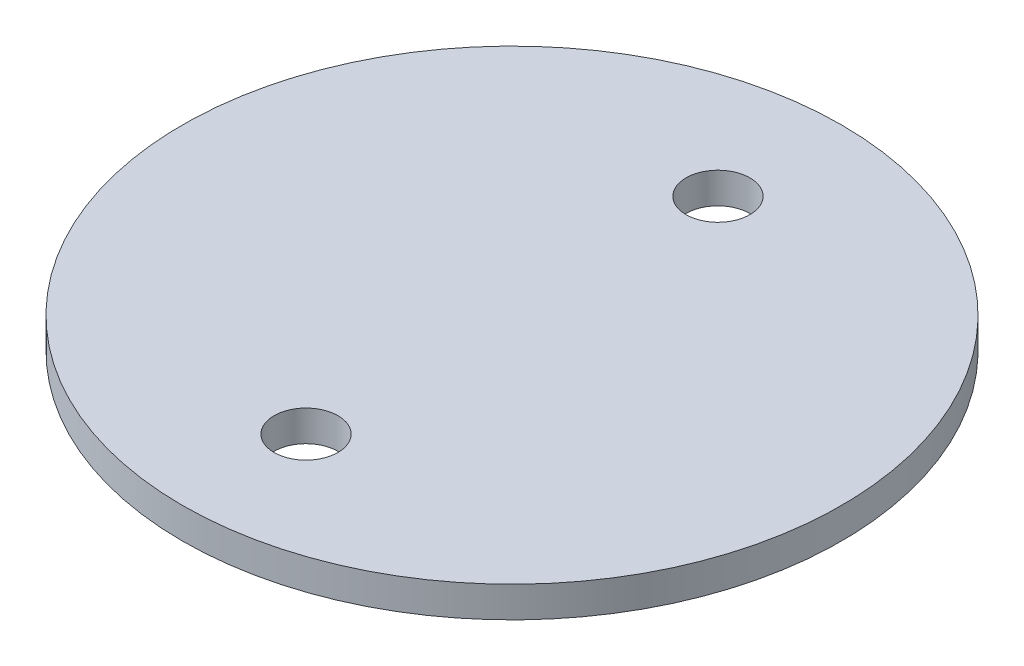
SolidWorks part; units mm, degrees
ref_plane "Front Plane" through (0, 0, 0) normal (0, 0, 1) x (1, 0, 0)
ref_plane "Top Plane" through (0, 0, 0) normal (0, 1, 0) x (1, 0, 0)
ref_plane "Right Plane" through (0, 0, 0) normal (1, 0, 0) x (0, 0, -1)
sketch "Sketch1" plane through (0, 0, 0) normal (0, 1, 0) x (1, 0, 0)
  line L0 (0, -20) -> (0, 20)
  circle A0 centre (0, 0) radius 32
  circle A1 centre (0, 20) radius 3.1
  circle A2 centre (0, -20) radius 3.1
  point P6 (0, 0)
  dimension "D1" = 64
  dimension "D3" = 6.2
  dimension "D2" = 40
extrude "Boss-Extrude1" add sketch "Sketch1" along normal blind 3
